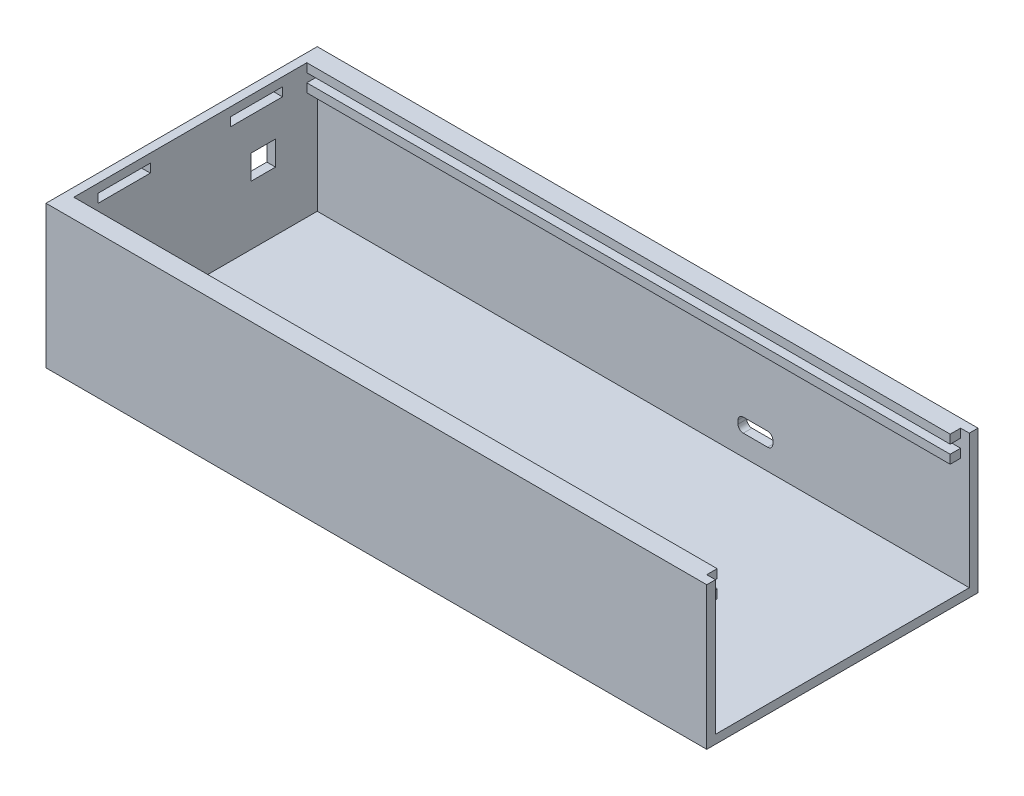
SolidWorks part; units mm, degrees
ref_plane "前视基准面" through (0, 0, 0) normal (0, 0, 1) x (1, 0, 0)
ref_plane "上视基准面" through (0, 0, 0) normal (0, 1, 0) x (1, 0, 0)
ref_plane "右视基准面" through (0, 0, 0) normal (1, 0, 0) x (0, 0, -1)
other "Configuration Table"
sketch "草图1" plane through (0, 0, 0) normal (0, 1, 0) x (1, 0, 0)
  line L1 (-83.8072, 28.741) -> (106.1928, 28.741)
  line L2 (-83.8072, 28.741) -> (-83.8072, -49.259)
  line L3 (-83.8072, -49.259) -> (106.1928, -49.259)
  line L4 (106.1928, 28.741) -> (106.1928, -49.259)
  dimension "D1" = 190
  dimension "D2" = 78
extrude "凸台-拉伸1" add sketch "草图1" along normal blind 41 contours L2 L1 L4 L3
sketch "草图2" plane through (0, 41, 0) normal (0, 1, 0) x (1, 0, 0)
  line L0 (-83.8072, 28.741) -> (-83.8072, -49.259) construction
  line L1 (-81.3072, 26.241) -> (103.6928, 26.241)
  line L2 (-81.3072, 26.241) -> (-81.3072, -46.759)
  line L3 (-81.3072, -46.759) -> (103.6928, -46.759)
  line L4 (103.6928, 26.241) -> (103.6928, -46.759)
  line L5 (-83.8072, 28.741) -> (106.1928, 28.741) construction
  line L6 (-83.8072, -49.259) -> (106.1928, -49.259) construction
  line L7 (106.1928, 28.741) -> (106.1928, -49.259) construction
  dimension "D1" = 2.5
  dimension "D2" = 2.5
  dimension "D3" = 2.5
  dimension "D4" = 2.5
extrude "切除-拉伸1" cut sketch "草图2" against normal blind 38.5 contours L2 L1 L4 L3
sketch "草图3" plane through (0, 41, 0) normal (0, 1, 0) x (1, 0, 0)
  line L0 (103.6928, 26.241) -> (103.6928, -46.759) construction
  line L5 (106.1928, 28.741) -> (106.1928, -49.259) construction
  line L6 (103.6928, 26.241) -> (106.1928, 26.241)
  line L7 (103.6928, 26.241) -> (103.6928, -46.759)
  line L8 (103.6928, -46.759) -> (106.1928, -46.759)
  line L9 (106.1928, 26.241) -> (106.1928, -46.759)
  line L10 (103.6928, 26.241) -> (103.6928, -46.759) construction
  point P4 (0, 0)
  point P7 (103.6928, -46.759)
extrude "切除-拉伸2" cut sketch "草图3" against normal blind 38.5
sketch "草图4" plane through (-83.8072, 0, 0) normal (-1, 0, 0) x (0, 0, 1)
  line L0 (-28.741, 0) -> (49.259, 0) construction
  line L1 (-14.241, 26.5) -> (-7.241, 26.5)
  line L2 (-14.241, 26.5) -> (-14.241, 19.5)
  line L3 (-14.241, 19.5) -> (-7.241, 19.5)
  line L4 (-7.241, 26.5) -> (-7.241, 19.5)
  line L5 (29.559, 26.5) -> (36.559, 26.5)
  line L6 (29.559, 26.5) -> (29.559, 19.5)
  line L7 (29.559, 19.5) -> (36.559, 19.5)
  line L8 (36.559, 26.5) -> (36.559, 19.5)
  line L9 (-28.741, 41) -> (-28.741, 0) construction
  dimension "D1" = 36.8
  dimension "D2" = 7
  dimension "D3" = 7
  dimension "D4" = 7
  dimension "D5" = 7
  dimension "D6" = 19.5
  dimension "D7" = 14.5
  dimension "D8" = 19.5
extrude "切除-拉伸4" cut sketch "草图4" against normal blind 2.5
sketch "草图5" plane through (0, 0, -28.741) normal (0, 0, -1) x (-1, 0, 0)
  line L0 (83.8072, 41) -> (83.8072, 0) construction
  line L1 (-39.6928, 8.5) -> (-49.6928, 8.5)
  line L2 (-39.6928, 8.5) -> (-39.6928, 12.5)
  line L3 (-39.6928, 12.5) -> (-49.6928, 12.5)
  line L4 (-49.6928, 8.5) -> (-49.6928, 12.5)
  line L5 (83.8072, 0) -> (-106.1928, 0) construction
  dimension "D1" = 123.5
  dimension "D2" = 8.5
  dimension "D3" = 10
  dimension "D4" = 4
extrude "切除-拉伸5" cut sketch "草图5" against normal blind 2.5
fillet "圆角1" radius 1.5 4 edges at (49.6928, 8.5, -27.491) (39.6928, 8.5, -27.491) (39.6928, 12.5, -27.491) (49.6928, 12.5, -27.491)
sketch "草图9" plane through (-81.3072, 0, 0) normal (1, 0, 0) x (0, 0, -1)
  line L11 (26.241, 41) -> (-46.759, 41) construction
  line L12 (-36.759, 38.5) -> (-21.759, 38.5)
  line L13 (-36.759, 38.5) -> (-36.759, 36)
  line L14 (-36.759, 36) -> (-21.759, 36)
  line L15 (-21.759, 38.5) -> (-21.759, 36)
  line L16 (1.241, 38.5) -> (16.241, 38.5)
  line L17 (1.241, 38.5) -> (1.241, 36)
  line L18 (1.241, 36) -> (16.241, 36)
  line L19 (16.241, 38.5) -> (16.241, 36)
  line L20 (-46.759, 2.5) -> (-46.759, 41) construction
  line L21 (26.241, 2.5) -> (26.241, 41) construction
  dimension "D1" = 15
  dimension "D2" = 2.5
  dimension "D3" = 2.5
  dimension "D4" = 10
  dimension "D5" = 15
  dimension "D6" = 2.5
  dimension "D7" = 2.5
  dimension "D8" = 10
extrude "切除-拉伸8" cut sketch "草图9" against normal blind 2.5
sketch "草图10" plane through (0, 0, 46.759) normal (0, 0, -1) x (-1, 0, 0)
  line L5 (81.3072, 41) -> (-103.6928, 41)
  line L6 (81.3072, 41) -> (81.3072, 38.5)
  line L7 (81.3072, 38.5) -> (-103.6928, 38.5)
  line L8 (-103.6928, 41) -> (-103.6928, 38.5)
  dimension "D1" = 185
  dimension "D2" = 2.5
extrude "凸台-拉伸2" add sketch "草图10" along normal blind 3
sketch "草图11" plane through (0, 0, -26.241) normal (0, 0, 1) x (1, 0, 0)
  line L1 (-81.3072, 41) -> (103.6928, 41)
  line L2 (-81.3072, 41) -> (-81.3072, 38.5)
  line L3 (-81.3072, 38.5) -> (103.6928, 38.5)
  line L4 (103.6928, 41) -> (103.6928, 38.5)
  dimension "D1" = 185
  dimension "D2" = 2.5
extrude "凸台-拉伸3" add sketch "草图11" along normal blind 3
sketch "草图12" plane through (0, 0, 46.759) normal (0, 0, -1) x (-1, 0, 0)
  line L0 (81.3072, 2.5) -> (81.3072, 38.5) construction
  line L1 (81.3072, 36) -> (-103.6928, 36)
  line L2 (81.3072, 36) -> (81.3072, 33.5)
  line L3 (81.3072, 33.5) -> (-103.6928, 33.5)
  line L4 (-103.6928, 36) -> (-103.6928, 33.5)
  line L5 (-103.6928, 38.5) -> (81.3072, 38.5) construction
  dimension "D1" = 185
  dimension "D2" = 2.5
  dimension "D3" = 2.5
extrude "凸台-拉伸4" add sketch "草图12" along normal blind 3
sketch "草图13" plane through (0, 0, -26.241) normal (0, 0, 1) x (1, 0, 0)
  line L0 (-81.3072, 2.5) -> (-81.3072, 38.5) construction
  line L1 (-81.3072, 36) -> (103.6928, 36)
  line L2 (-81.3072, 36) -> (-81.3072, 33.5)
  line L3 (-81.3072, 33.5) -> (103.6928, 33.5)
  line L4 (103.6928, 36) -> (103.6928, 33.5)
  line L5 (-81.3072, 38.5) -> (103.6928, 38.5) construction
  dimension "D1" = 185
  dimension "D2" = 2.5
  dimension "D3" = 2.5
extrude "凸台-拉伸5" add sketch "草图13" along normal blind 3
